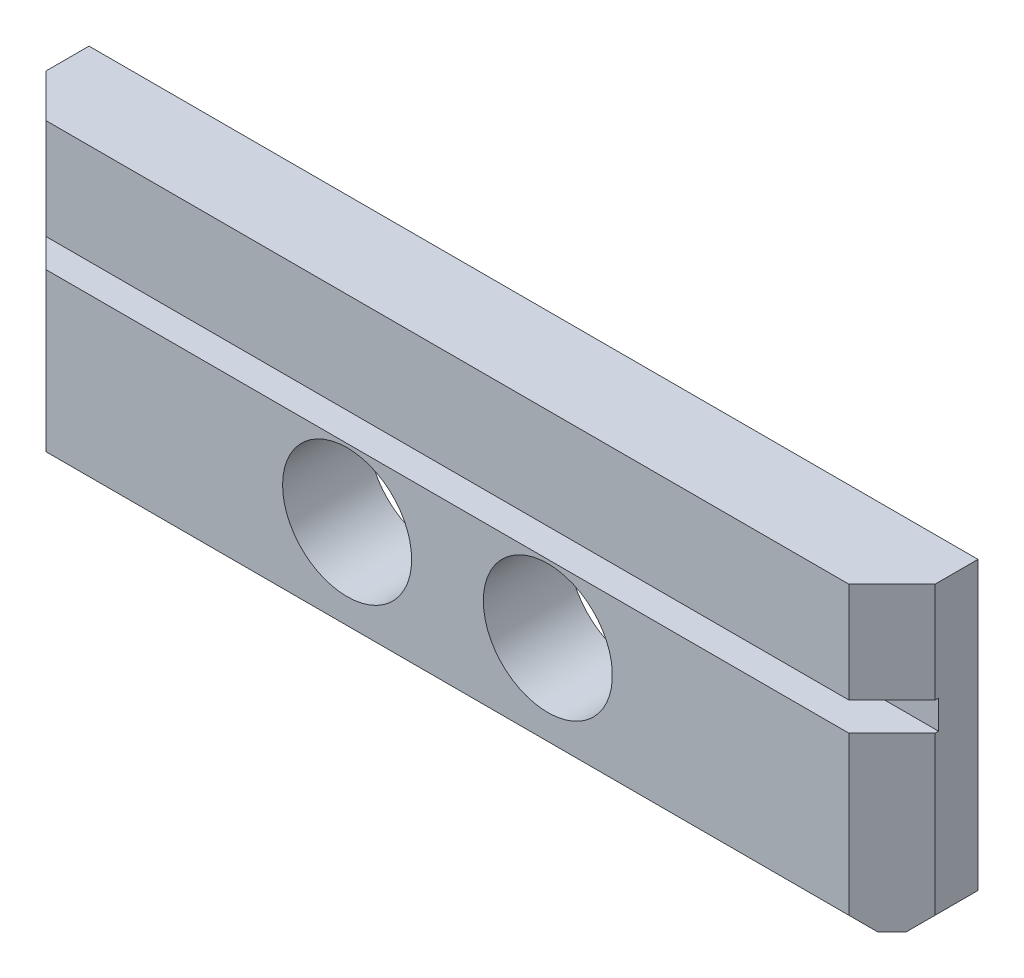
SolidWorks part; units mm, degrees
ref_plane "Front Plane" through (0, 0, 0) normal (0, 0, 1) x (1, 0, 0)
ref_plane "Top Plane" through (0, 0, 0) normal (0, 1, 0) x (1, 0, 0)
ref_plane "Right Plane" through (0, 0, 0) normal (1, 0, 0) x (0, 0, -1)
ref_plane "Inside of pax case" through (0, 1.6002, 0) normal (0, 1, 0) x (-1, 0, 0)
sketch "Sketch1" plane through (0, 1.6002, 0) normal (0, 1, 0) x (1, 0, 0)
  line L1 (-196.85, 39.7002) -> (196.85, 39.7002)
  line L2 (-196.85, 39.7002) -> (-196.85, 1.6002)
  line L3 (-196.85, 1.6002) -> (196.85, 1.6002)
  line L4 (196.85, 39.7002) -> (196.85, 1.6002)
  point P4 (0, 1.6002)
  dimension "D1" = 1.6002
  dimension "D2" = 393.7
  dimension "D3" = 38.1
extrude "Extrude1" add sketch "Sketch1" along normal blind 133.35
chamfer "Chamfer1" distance 19.05 angle 45 2 edges at (196.85, 68.2752, -1.6002) (-196.85, 68.2752, -1.6002)
chamfer "Chamfer2" distance 6.35 angle 45 3 edges at (-196.85, 1.6002, -30.1752) (0, 1.6002, -1.6002) (196.85, 1.6002, -30.1752)
sketch "Sketch2" plane through (0, 0, 0) normal (0, 0, 1) x (1, 0, 0)
  line L0 (0, 0) -> (0, 72.5046) construction
  circle A0 centre (-44.45, 47.625) radius 28.575
  circle A1 centre (44.45, 47.625) radius 28.575
  dimension "D3" = 57.15
  dimension "D2" = 47.625
  dimension "D1" = 88.9
extrude "Cut-Extrude1" cut sketch "Sketch2" against normal through all
sketch "Sketch3" plane through (0, 0, 0) normal (0, 0, 1) x (1, 0, 0)
  line L1 (-203.2574, 90.5002) -> (203.2574, 90.5002)
  line L2 (-203.2574, 90.5002) -> (-203.2574, 77.8002)
  line L3 (-203.2574, 77.8002) -> (203.2574, 77.8002)
  line L4 (203.2574, 90.5002) -> (203.2574, 77.8002)
  point P4 (0, 77.8002)
  dimension "D1" = 77.8002
  dimension "D2" = 12.7
extrude "Cut-Extrude2" cut sketch "Sketch3" against normal blind 22.225
chamfer "Chamfer3" [suppressed] distance 3.175 angle 45
